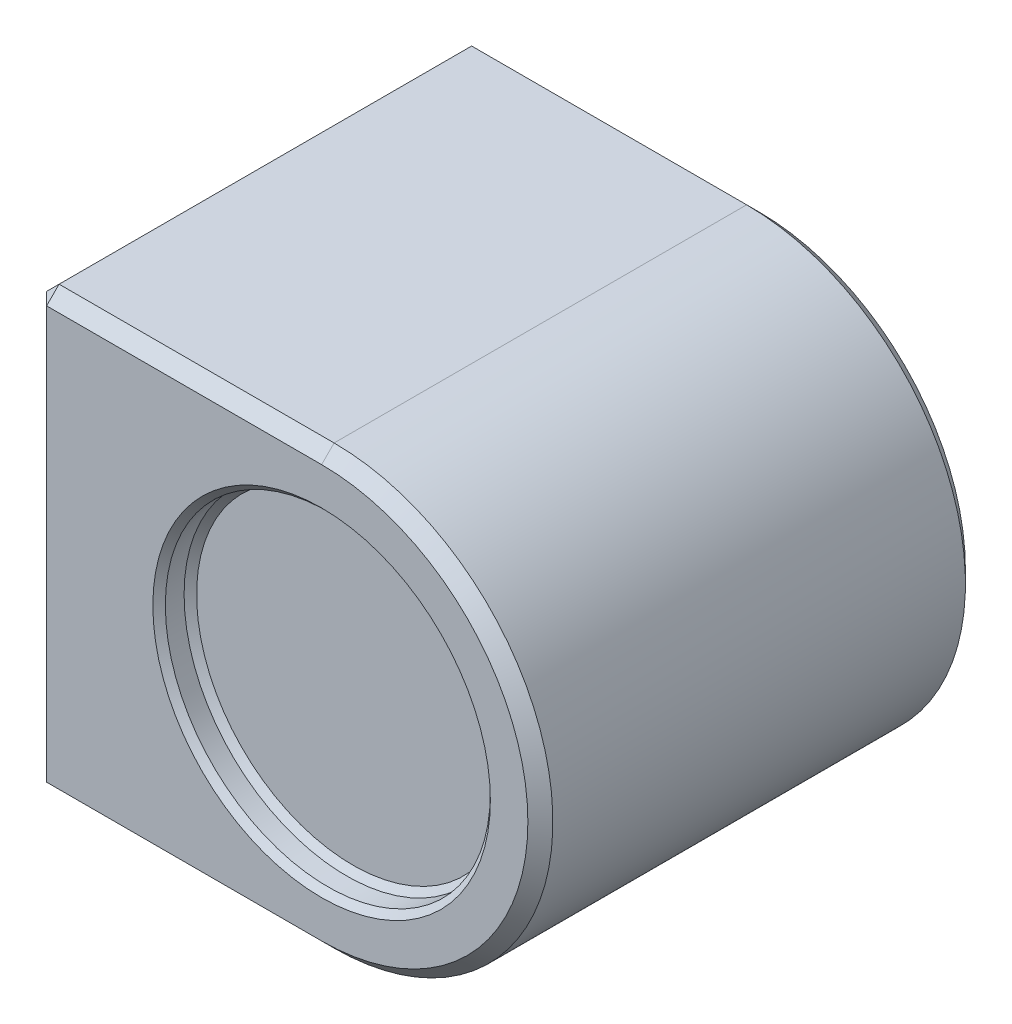
SolidWorks part; units mm, degrees
ref_plane "Front Plane" through (0, 0, 0) normal (0, 0, 1) x (1, 0, 0)
ref_plane "Top Plane" through (0, 0, 0) normal (0, 1, 0) x (1, 0, 0)
ref_plane "Right Plane" through (0, 0, 0) normal (1, 0, 0) x (0, 0, -1)
sketch "Sketch3" plane through (0, 0, 0) normal (0, 0, 1) x (1, 0, 0)
  line L0 (0, 35) -> (46, 35)
  line L1 (46, 35) -> (46, -35)
  line L2 (46, -35) -> (0, -35)
  arc A0 (0, 35) -> (0, -35) centre (0, 0) ccw
  dimension "D1" = 70
  dimension "D2" = 46
extrude "Boss-Extrude1" add sketch "Sketch3" along normal blind 70
sketch "Sketch4" plane through (46, 0, 0) normal (1, 0, 0) x (0, 0, -1)
  line L0 (0, 0) -> (-70, 0) construction
  line L1 (-70, -35) -> (-70, 35) construction
  circle A0 centre (-38, 0) radius 25
  dimension "D1" = 50
  dimension "D2" = 32
extrude "Boss-Extrude2" add sketch "Sketch4" along normal blind 5
sketch "Sketch5" plane through (0, 0, 0) normal (0, 0, -1) x (-1, 0, 0)
  circle A0 centre (0, 0) radius 26
  dimension "D1" = 52
chamfer "Chamfer1" distance 2 angle 45 10 edges at (23, -35, 0) (-35, 0, 0) (23, 35, 0) (46, -35, 35) (46, 0, 0) (46, 35, 35) (23, 35, 70) (46, 0, 70) (23, -35, 70) (-35, 0, 70)
extrude "Cut-Extrude1" cut sketch "Sketch5" against normal blind 5
chamfer "Chamfer3" distance 1 angle 45 4 edges at (-26, 0, 5) (51, 0, 13) (46, 0, 63) (-26, 0, 0)
mirror "Mirror1" about plane through (0, 0, 0) normal (1, 0, 0) of bodies 104
delete or keep bodies "Body-Delete/Keep 1" type delete bodies bodies 104
mirror "Mirror2" about plane through (0, 0, 0) normal (0, 0, 1) of bodies 105
delete or keep bodies "Body-Delete/Keep 2" type delete bodies bodies 105
sketch "Sketch6" plane through (0, 0, 0) normal (0, 1, 0) x (1, 0, 0)
  line L0 (35, 35) -> (-51, 35) construction
  line L1 (35, 2) -> (35, 68) construction
  line L2 (-51, 62) -> (-51, 14) construction
  point P6 (-8, 35)
